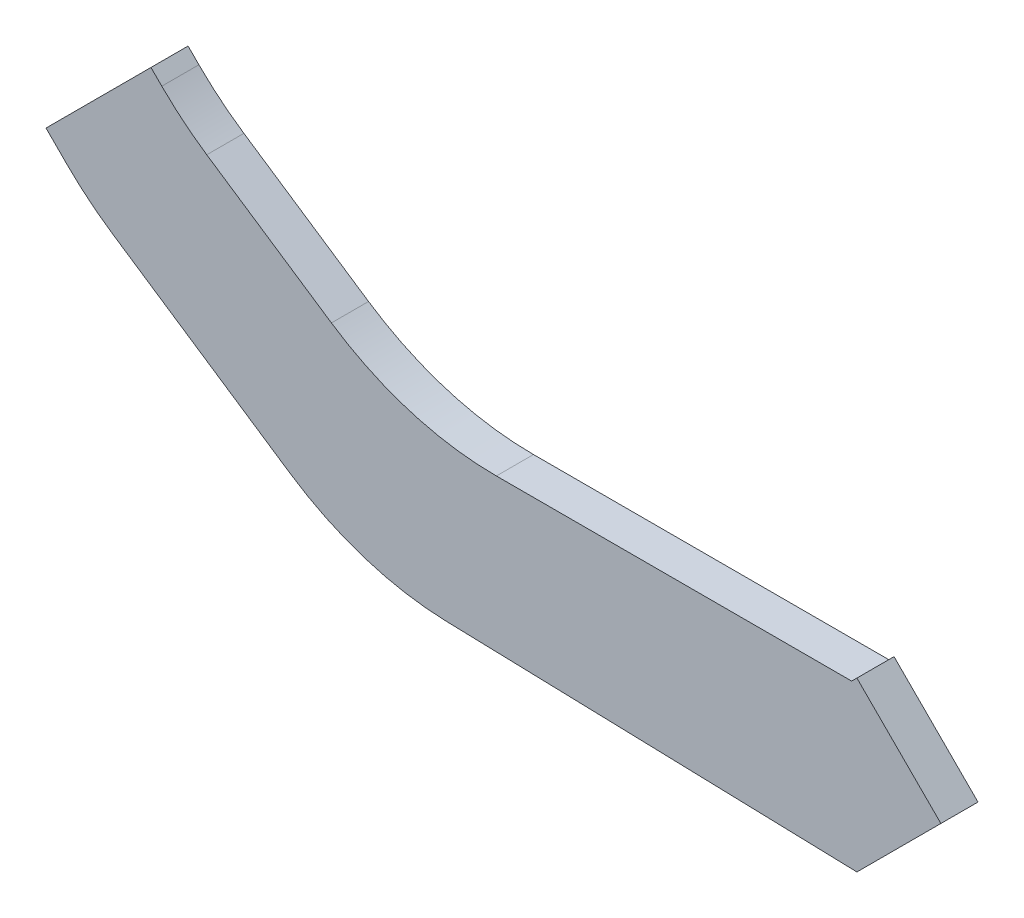
SolidWorks part; units mm, degrees
material "PBT General Purpose"
ref_plane "Front Plane" through (0, 0, 0) normal (0, 0, 1) x (1, 0, 0)
ref_plane "Top Plane" through (0, 0, 0) normal (0, 1, 0) x (1, 0, 0)
ref_plane "Right Plane" through (0, 0, 0) normal (1, 0, 0) x (0, 0, -1)
sketch "frame_outline" plane through (0, 0, 0) normal (0, 0, 1) x (1, 0, 0)
  line L0 (-1.8031, -1.8738) -> (-1.591, -2.086)
  line L1 (0, 0) -> (0.3, 0) construction
  line L2 (-2.5102, -2.5809) -> (-2.2285, -2.8627)
  line L3 (0, 0) -> (4.9667, -4.9667) construction
  line L84 (-1.591, -2.086) -> (-0.0832, -3.0936)
  line L85 (-2.2285, -2.8627) -> (-0.3866, -4.0936)
  line L87 (0, 0) -> (-3.6266, -3.6266) construction
  line L88 (2.9522, -3.0582) -> (3.5179, -3.6239)
  line L89 (2.9522, -3.0582) -> (2.9168, -3.0936)
  line L90 (2.9168, -3.0936) -> (-0.0832, -3.0936)
  line L91 (3.5179, -3.6239) -> (2.9522, -4.1896)
  line L92 (-1.8031, -1.8738) -> (-2.5102, -2.5809)
  line L93 (-0.3866, -4.0936) -> (2.9522, -4.1896)
  dimension "D2" = 0.3
  dimension "D4" = 45
  dimension "D18" = 45
  dimension "D19" = 0.075
  dimension "D20" = 0.05
  dimension "D17" = 4.25
  dimension "D21" = 0.8
  dimension "D22" = 0.8
  dimension "D23" = 1
  dimension "D24" = 0.05
  dimension "D3" = 2.6
  dimension "D5" = 3
  dimension "D6" = 0.3
  dimension "D7" = 1
  dimension "D8" = 1
extrude "Boss-Extrude1" add sketch "frame_outline" along normal mid plane 0.25
fillet "Fillet1" radius 2 4 edges at (-2.2285, -2.8627, 0) (-0.3866, -4.0936, 0) (-1.591, -2.086, 0) (-0.0832, -3.0936, 0)
equation "\"t\"= 0.25'thickness of the sheets"
equation "\"t_cf\"= 0.115'thickness of single carbon fiber layer"
equation "\"t_kapton\"= 0.025'thickness of single Kapton flex layer"
equation "\"t_fr4\"= 0.1'thickness of FR4 with copper layer"
equation "\"joint_flex\"= 0.1'Width of flextures gap"
equation "\"joint_flex_eff\"= 0.02'Width of flecture after castelation"
equation "\"joint_fold\"= 0.2'Width of folding joints for 90deg fold"
equation "\"gap_tolerance\"= 0.002'Width to have interfecence fit between carbon fiber inserts"
equation "\"assemble_angle\"= 90'Angle of assembly parts"
equation "\"D1@Boss-Extrude1\"=\"t\""
equation "\"link_lift\"= 0.5'Actuation linkage amplification for the lift motion"
equation "\"link_swing\"= 0.45'Actuation linkage amplification for the swing motion"
equation "\"D19@frame_outline\"=\"joint_fold\"-\"t\"/2"
equation "\"D17@frame_outline\"=4.2+0.05"
equation "\"D24@frame_outline\"=\"joint_flex\"/2"
